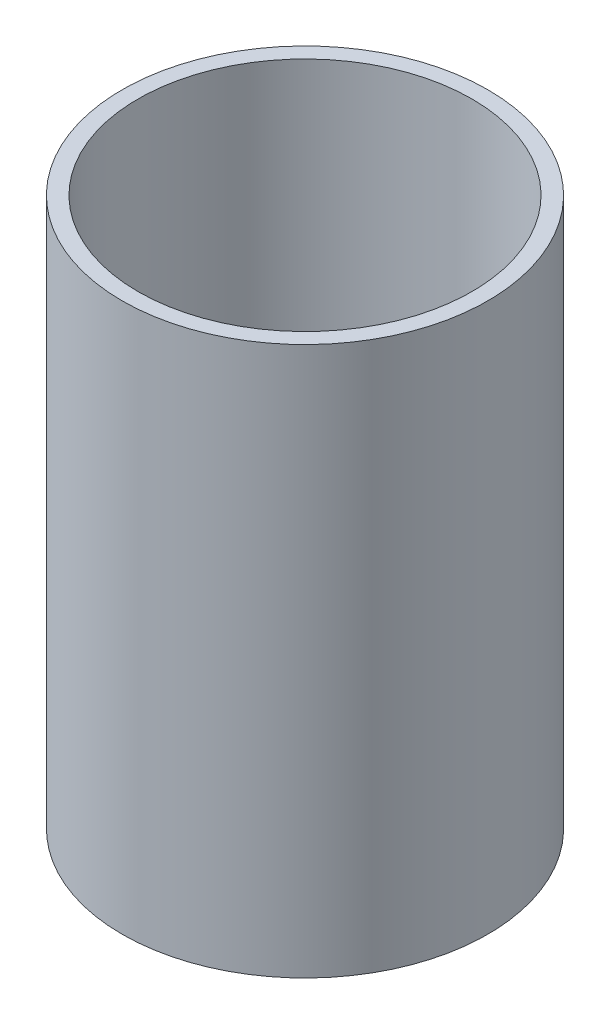
SolidWorks part; units mm, degrees
material "PTFE (general)"
ref_plane "Front Plane" through (0, 0, 0) normal (0, 0, 1) x (1, 0, 0)
ref_plane "Top Plane" through (0, 0, 0) normal (0, 1, 0) x (1, 0, 0)
ref_plane "Right Plane" through (0, 0, 0) normal (1, 0, 0) x (0, 0, -1)
sketch "Sketch1" plane through (0, 0, 0) normal (0, 1, 0) x (0.9999, 0, -0.0151)
  circle A0 centre (-53.9124, 33.1593) radius 10.65
  circle A1 centre (-53.9124, 33.1593) radius 11.666
  dimension "D2" = 23.332
  dimension "D1" = 1.016
extrude "Boss-Extrude1" add sketch "Sketch1" along normal blind 35
